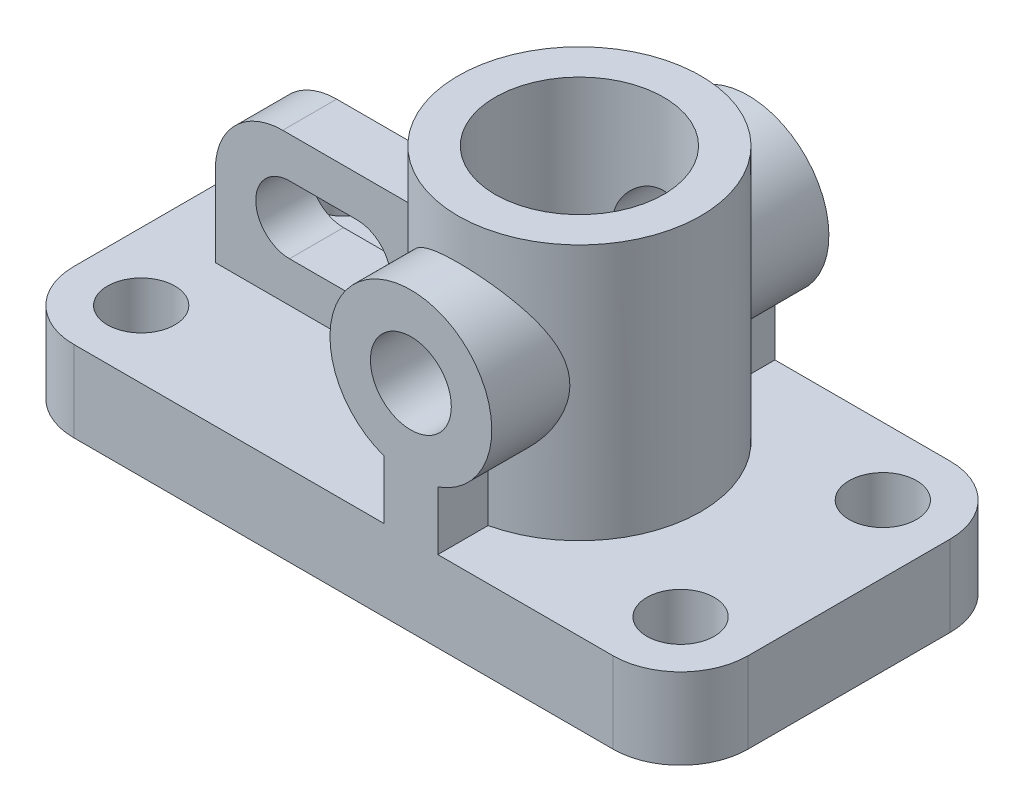
SolidWorks part; units mm, degrees
material "灰铸铁"
ref_plane "前视基准面" through (0, 0, 0) normal (0, 0, 1) x (1, 0, 0)
ref_plane "上视基准面" through (0, 0, 0) normal (0, 1, 0) x (1, 0, 0)
ref_plane "右视基准面" through (0, 0, 0) normal (1, 0, 0) x (0, 0, -1)
sketch "草图1" plane through (0, 0, 0) normal (0, 1, 0) x (1, 0, 0)
  line L0 (-57.4689, 0) -> (58.5973, 0) construction
  line L1 (0, 57.9323) -> (0, -56.6933) construction
  line L3 (-50, -25) -> (30, -25)
  line L4 (-60, -15) -> (-60, 15)
  line L5 (-50, 25) -> (30, 25)
  line L6 (40, -15) -> (40, 15)
  arc A0 (-50, -25) -> (-60, -15) centre (-50, -15) cw
  arc A1 (30, -25) -> (40, -15) centre (30, -15) ccw
  arc A2 (30, 25) -> (40, 15) centre (30, 15) cw
  arc A3 (-60, 15) -> (-50, 25) centre (-50, 15) cw
  dimension "D1" = 10
  dimension "D2" = 100
  dimension "D3" = 60
  dimension "D4" = 50
extrude "凸台-拉伸1" add sketch "草图1" along normal blind 12
sketch "草图2" plane through (0, 0, 0) normal (0, 0, 1) x (1, 0, 0)
  line L0 (0, 42.9855) -> (0, 0) construction
  line L1 (-50, 12) -> (30, 12) construction
  line L2 (0, 0) -> (18, 0)
  line L3 (0, 0) -> (0, 50)
  line L4 (0, 50) -> (18, 50)
  line L5 (18, 0) -> (18, 50)
  dimension "D1" = 36
  dimension "D2" = 38
revolve "旋转1" add sketch "草图2" angle 360 about L0
sketch "草图3" plane through (0, 0, 0) normal (0, 0, 1) x (1, 0, 0)
  line L0 (0, 75.673) -> (0, -23.6919) construction
  line L2 (-50, 0) -> (30, 0) construction
  circle A0 centre (0, 32) radius 12
  dimension "D1" = 24
  dimension "D2" = 32
extrude "凸台-拉伸3" add sketch "草图3" along normal up to surface and the other way up to surface up to face at (-10, 6, 25) other way up to face at (-10, 6, -25)
sketch "草图4" plane through (0, 0, 0) normal (0, 0, 1) x (1, 0, 0)
  line L0 (-50, 12) -> (30, 12) construction
  line L1 (-40, 34) -> (0, 34)
  line L2 (-50, 24) -> (-50, 12)
  line L3 (-50, 12) -> (0, 12)
  line L4 (0, 34) -> (0, 12)
  arc A0 (-40, 34) -> (-50, 24) centre (-40, 24) ccw
  dimension "D1" = 10
  dimension "D2" = 50
  dimension "D3" = 22
extrude "凸台-拉伸4" add sketch "草图4" along normal mid plane 8
sketch "草图5" plane through (0, 0, 0) normal (1, 0, 0) x (0, 0, -1)
  line L0 (-25, 20) -> (-25, 12)
rib "筋1" sketch "草图5" sketch "草图5" thickness 8 extrusion direction parallel to sketch draft on no parameters "D1"=8
mirror "镜向1" about plane through (0, 0, 0) normal (0, 0, 1) of "筋1"
hole_wizard "Ø10.0 (10) 直径孔1" positions "草图7" profile "草图6" hole size "Ø10.0" standard "GB" end condition through all
sketch "草图7" plane through (0, 12, 0) normal (0, 1, 0) x (1, 0, 0)
  point P0 (-50, -15)
sketch "草图6" plane through (-50, 12, 15) normal (1, 0, 0) x (0, 0, 1)
  line L0 (0, 0) -> (0, 12)
  line L1 (0, 12) -> (5, 12)
  line L2 (5, 12) -> (5, 0)
  line L5 (5, 0) -> (0, 0)
  line L11 (0, -6.35) -> (0, 107.95) construction
  dimension "通孔孔直径" = 10
  dimension "通孔孔深度" = 12
pattern_linear "阵列(线性)2" count 2 spacing 80 along (1, 0, 0) count 2 spacing 30 along (0, 0, -1) of "Ø10.0 (10) 直径孔1"
sketch "草图8" plane through (0, 0, 4) normal (0, 0, 1) x (1, 0, 0)
  line L0 (-39, 23) -> (-29, 23) construction
  line L1 (-39, 18) -> (-29, 18)
  line L2 (-39, 28) -> (-29, 28)
  line L3 (-50, 12) -> (-17.5499, 12) construction
  line L4 (-50, 24) -> (-50, 12) construction
  arc A0 (-39, 18) -> (-39, 28) centre (-39, 23) cw
  arc A1 (-29, 18) -> (-29, 28) centre (-29, 23) ccw
  dimension "D4" = 6
  dimension "D3" = 20
  dimension "D1" = 10
  dimension "D2" = 11
extrude "切除-拉伸1" cut sketch "草图8" against normal through all
hole_wizard "Ø25.0 (25) 直径孔1" positions "草图10" profile "草图9" hole size "Ø25.0" standard "GB" end condition through all
sketch "草图10" plane through (0, 50, 0) normal (0, 1, 0) x (1, 0, 0)
  point P0 (0, 0)
sketch "草图9" plane through (0, 50, 0) normal (1, 0, 0) x (0, 0, 1)
  line L0 (0, 0) -> (0, 50)
  line L1 (0, 50) -> (12.5, 50)
  line L2 (12.5, 50) -> (12.5, 0)
  line L5 (12.5, 0) -> (0, 0)
  line L11 (0, -6.35) -> (0, 107.95) construction
  dimension "通孔孔直径" = 25
  dimension "通孔孔深度" = 50
hole_wizard "Ø12.0 (12) 直径孔1" positions "草图12" profile "草图11" hole size "Ø12.0" standard "GB" end condition through all
sketch "草图12" plane through (0, 0, 25) normal (0, 0, 1) x (1, 0, 0)
  point P0 (0, 32)
sketch "草图11" plane through (0, 32, 25) normal (1, 0, 0) x (0, -1, 0)
  line L0 (0, 0) -> (0, 50)
  line L1 (0, 50) -> (6, 50)
  line L2 (6, 50) -> (6, 0)
  line L5 (6, 0) -> (0, 0)
  line L11 (0, -6.35) -> (0, 107.95) construction
  dimension "通孔孔直径" = 12
  dimension "通孔孔深度" = 50
fillet "圆角1" [suppressed] radius 2
chamfer "倒角1" [suppressed] distance 1
